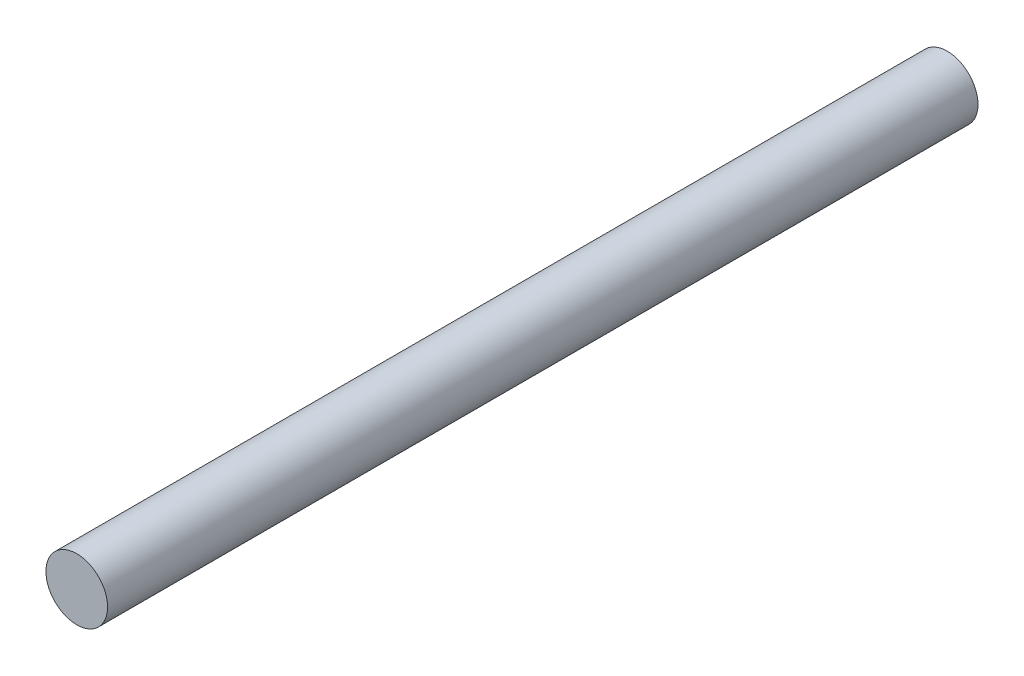
SolidWorks part; units mm, degrees
ref_plane "Front Plane" through (0, 0, 0) normal (0, 0, 1) x (1, 0, 0)
ref_plane "Top Plane" through (0, 0, 0) normal (0, 1, 0) x (1, 0, 0)
ref_plane "Right Plane" through (0, 0, 0) normal (1, 0, 0) x (0, 0, -1)
sketch "Sketch1" plane through (0, 0, 0) normal (0, 0, 1) x (1, 0, 0)
  circle A0 centre (0, 0) radius 4
  dimension "D1" = 8
extrude "Boss-Extrude1" add sketch "Sketch1" along normal blind 113
